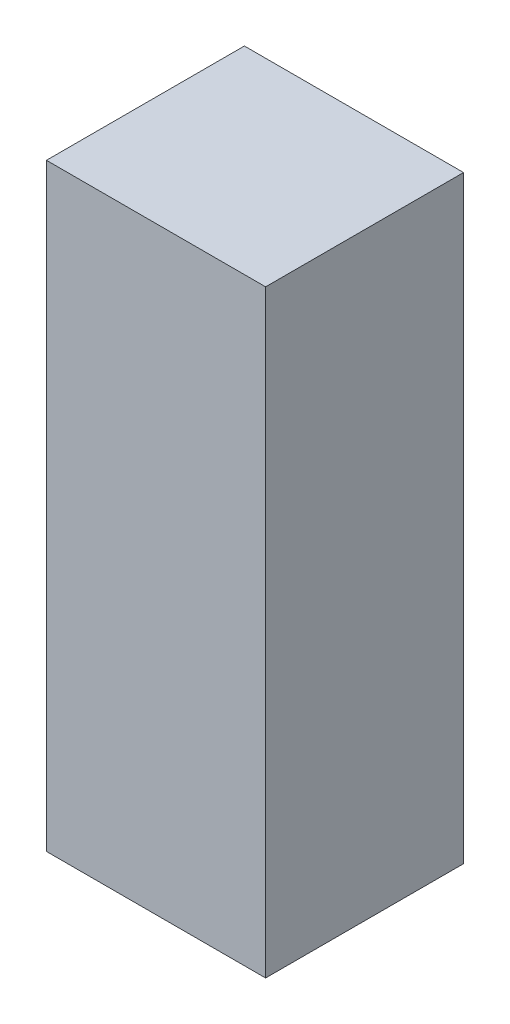
SolidWorks part; units mm, degrees
ref_plane "Front Plane" through (0, 0, 0) normal (0, 0, 1) x (1, 0, 0)
ref_plane "Top Plane" through (0, 0, 0) normal (0, 1, 0) x (1, 0, 0)
ref_plane "Right Plane" through (0, 0, 0) normal (1, 0, 0) x (0, 0, -1)
sketch "Sketch1" plane through (0, 0, 0) normal (0, 1, 0) x (1, 0, 0)
  line L1 (-41.6478, 59.4391) -> (51.3522, 59.4391)
  line L2 (-41.6478, 59.4391) -> (-41.6478, -24.5609)
  line L3 (-41.6478, -24.5609) -> (51.3522, -24.5609)
  line L4 (51.3522, 59.4391) -> (51.3522, -24.5609)
  dimension "D1" = 93
  dimension "D2" = 84
extrude "Boss-Extrude1" add sketch "Sketch1" along normal blind 254
